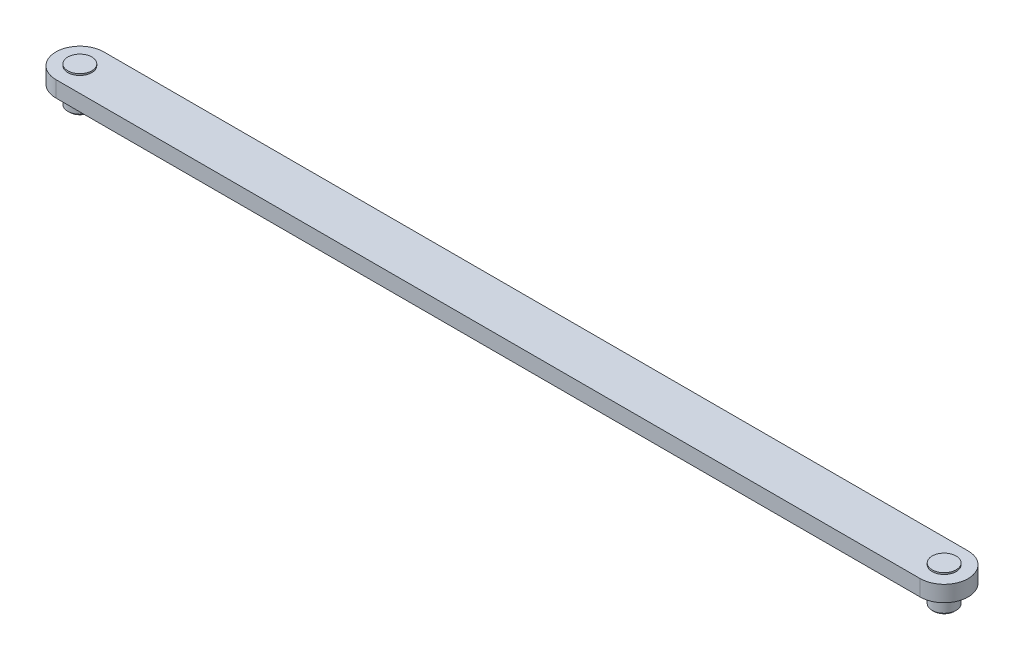
SolidWorks part; units mm, degrees
ref_plane "Front Plane" through (0, 0, 0) normal (0, 0, 1) x (1, 0, 0)
ref_plane "Top Plane" through (0, 0, 0) normal (0, 1, 0) x (1, 0, 0)
ref_plane "Right Plane" through (0, 0, 0) normal (1, 0, 0) x (0, 0, -1)
sketch "Sketch2" plane through (0, 0, 0) normal (0, 1, 0) x (1, 0, 0)
  line L8 (-141.6479, 139.0209) -> (399.1221, 139.0209) construction
  line L9 (-141.6479, 154.0209) -> (399.1221, 154.0209)
  line L10 (-141.6479, 124.0209) -> (399.1221, 124.0209)
  arc A9 (-141.6479, 154.0209) -> (-141.6479, 124.0209) centre (-141.6479, 139.0209) ccw
  arc A10 (399.1221, 124.0209) -> (399.1221, 154.0209) centre (399.1221, 139.0209) ccw
  circle A11 centre (-141.6479, 139.0209) radius 7.5
  circle A12 centre (399.1221, 139.0209) radius 7.5
  point P12 (128.7371, 139.0209)
  dimension "D1" = 15
  dimension "D2" = 15
  dimension "D3" = 540.77
  dimension "D4" = 15
extrude "Boss-Extrude4" add sketch "Sketch2" along normal mid plane 10
sketch "Sketch5" plane through (0, 5, 0) normal (0, 1, 0) x (1, 0, 0)
  line L2 (-141.6479, 124.0209) -> (399.1221, 124.0209)
  line L3 (399.1221, 154.0209) -> (-141.6479, 154.0209)
  circle A0 centre (-141.6479, 139.0209) radius 7.5
  arc A2 (-141.6479, 154.0209) -> (-141.6479, 124.0209) centre (-141.6479, 139.0209) ccw
  arc A3 (399.1221, 124.0209) -> (399.1221, 154.0209) centre (399.1221, 139.0209) ccw
  arc A4 (-141.6479, 154.0209) -> (-141.6479, 124.0209) centre (-141.6479, 139.0209) ccw
  arc A5 (399.1221, 124.0209) -> (399.1221, 154.0209) centre (399.1221, 139.0209) ccw
  circle M5 centre (-141.6479, 139.0209) radius 7.5
  dimension "D2" = 15
  dimension "D1" = 0
extrude "Boss-Extrude5" add sketch "Sketch5" along normal blind 1 and the other way blind 22 contours M5
chamfer "Chamfer1" distance 1 angle 45 1 edges at (-141.6479, -17, -131.5209)
sketch "Sketch7" plane through (0, -5, 0) normal (0, -1, 0) x (-1, 0, 0)
  circle A0 centre (-399.1221, 139.0209) radius 7.5
sketch "Sketch8" plane through (0, 5, 0) normal (0, 1, 0) x (1, 0, 0)
  circle A1 centre (399.1221, 139.0209) radius 7.5
extrude "Boss-Extrude8" add sketch "Sketch8" along normal blind 1 and the other way blind 22
chamfer "Chamfer3" distance 1 angle 45 1 edges at (399.1221, -17, -131.5209)
